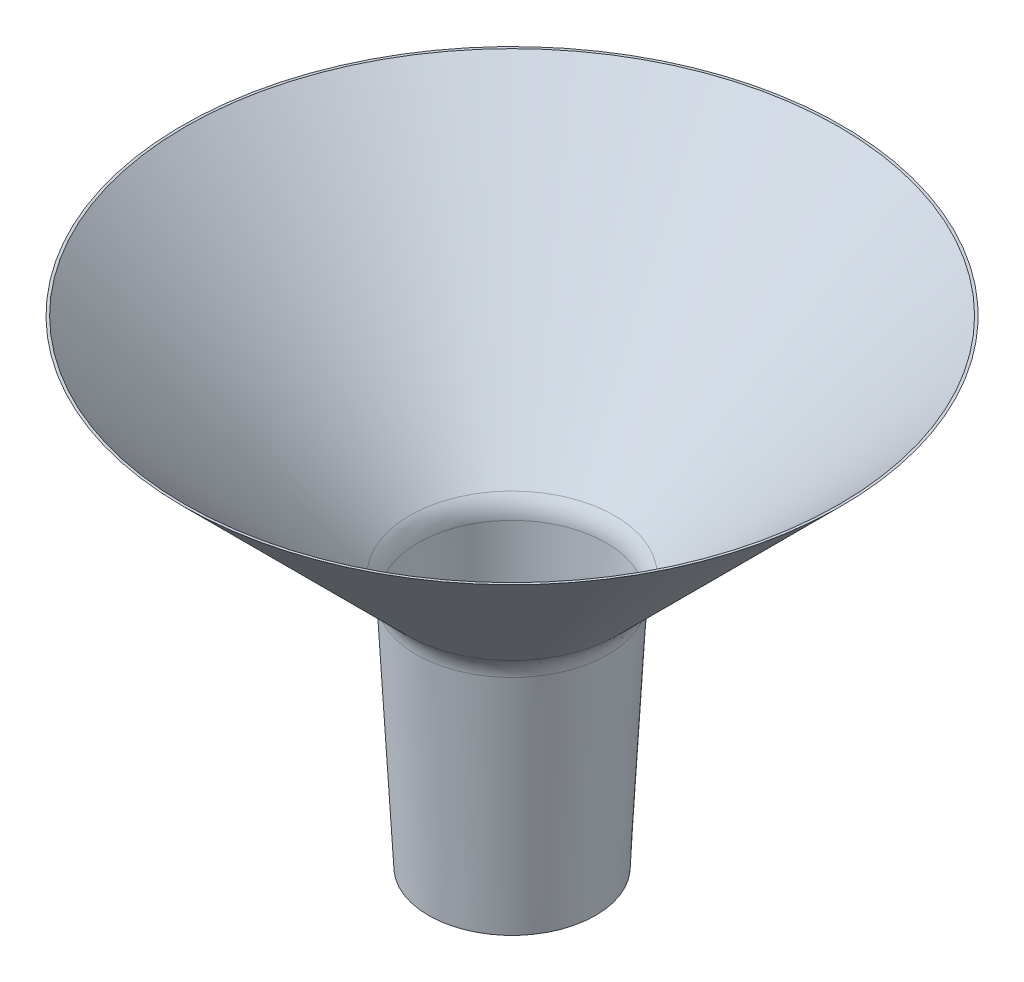
SolidWorks part; units mm, degrees
ref_plane "Front Plane" through (0, 0, 0) normal (0, 0, 1) x (1, 0, 0)
ref_plane "Top Plane" through (0, 0, 0) normal (0, 1, 0) x (1, 0, 0)
ref_plane "Right Plane" through (0, 0, 0) normal (1, 0, 0) x (0, 0, -1)
sketch "Sketch1" plane through (0, 0, 0) normal (0, 0, 1) x (1, 0, 0)
  line L0 (0, 0) -> (25, 0) construction
  line L1 (25, 0) -> (28.9306, 75)
  line L2 (28.9306, 75) -> (100, 146.0694)
  line L3 (100, 146.0694) -> (100.7778, 146.0694)
  line L4 (100.7778, 146.0694) -> (29.4688, 74.7604)
  line L5 (29.4688, 74.7604) -> (25.5508, 0)
  line L6 (25.5508, 0) -> (25, 0)
  line L7 (65.1233, 110.4149) -> (64.7344, 110.8038) construction
  line L8 (27.5098, 37.3802) -> (26.9605, 37.409) construction
  line L9 (0, 0.7781) -> (0, 50000.7781) construction
  line L10 (28.9306, 75) -> (0, 75) construction
  line L11 (25.5508, 0) -> (25.5508, 75) construction
  dimension "D2" = 25
  dimension "D1" = 0.55
  dimension "D3" = 100
  dimension "D5" = 45
  dimension "D4" = 75
  dimension "D6" = 93
  dimension "D7" = 146.0694
ref_axis "Axis1" through (0, -2.9, 0) along (0, 1, 0)
revolve "Revolve1" add sketch "Sketch1" angle 360 about axis through (0, -2.9, 0) along (0, 1, 0)
fillet "Fillet1" radius 10 1 edges at (0, 74.7604, -29.4688)
fillet "Fillet2" radius 9 1 edges at (0, 75, -28.9306)
equation "\"Spout_Tip\" = 25'Radius"
equation "\"D2@Sketch1\"=\"Spout_Tip\""
equation "\"Funnel_Enterance\"= 100'Radius"
equation "\"D3@Sketch1\"=\"Funnel_Enterance\""
equation "\"Spout_Length\"= 75"
equation "\"D4@Sketch1\"=\"Spout_Length\""
